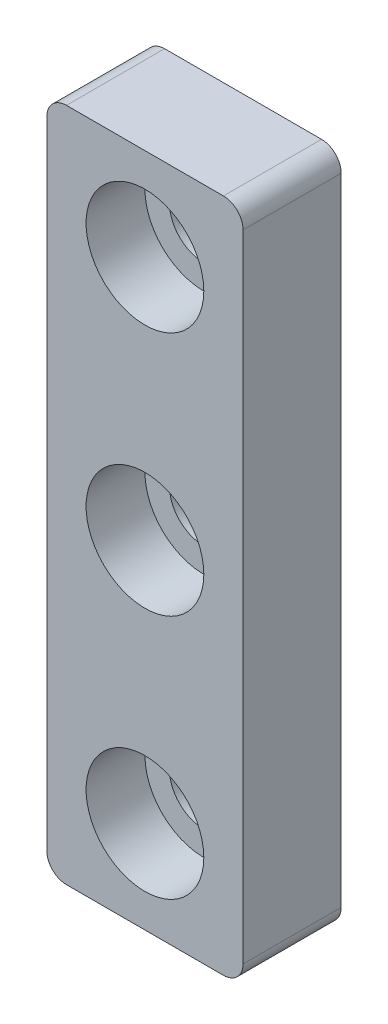
SolidWorks part; units mm, degrees
ref_plane "XY" through (0, 0, 0) normal (0, 0, 1) x (1, 0, 0)
ref_plane "XZ" through (0, 0, 0) normal (0, 1, 0) x (1, 0, 0)
ref_plane "YZ" through (0, 0, 0) normal (1, 0, 0) x (0, 0, -1)
sketch "Sketch1" plane through (0, 0, 0) normal (0, 0, 1) x (1, 0, 0)
  line L1 (5, 17.2) -> (-5, 17.2)
  line L2 (5, 17.2) -> (5, -17.2)
  line L3 (5, -17.2) -> (-5, -17.2)
  line L4 (-5, 17.2) -> (-5, -17.2)
  line L5 (5, 17.2) -> (-5, -17.2) construction
  line L6 (5, -17.2) -> (-5, 17.2) construction
  point P0 (0, 0)
  dimension "D1" = 10
  dimension "D2" = 34.4
extrude "Boss-Extrude1" add sketch "Sketch1" along normal blind 5
fillet "Fillet1" radius 1 4 edges at (-5, -17.2, 2.5) (5, -17.2, 2.5) (5, 17.2, 2.5) (-5, 17.2, 2.5)
sketch "Sketch4" plane through (0, 0, 5) normal (0, 0, 1) x (1, 0, 0)
  circle A0 centre (0, 0) radius 1.75
  circle A1 centre (0, 12.5) radius 1.75
  circle A2 centre (0, -12.5) radius 1.75
  dimension "D1" = 3.5
  dimension "D2" = 12.5
  dimension "D3" = 12.5
extrude "Cut-Extrude1" cut sketch "Sketch4" against normal blind 5
sketch "Sketch5" plane through (0, 0, 5) normal (0, 0, 1) x (1, 0, 0)
  circle A0 centre (0, 12.5) radius 3
  circle A1 centre (0, 0) radius 3
  circle A2 centre (0, -12.5) radius 3
  dimension "D1" = 6
extrude "Cut-Extrude2" cut sketch "Sketch5" against normal blind 3
